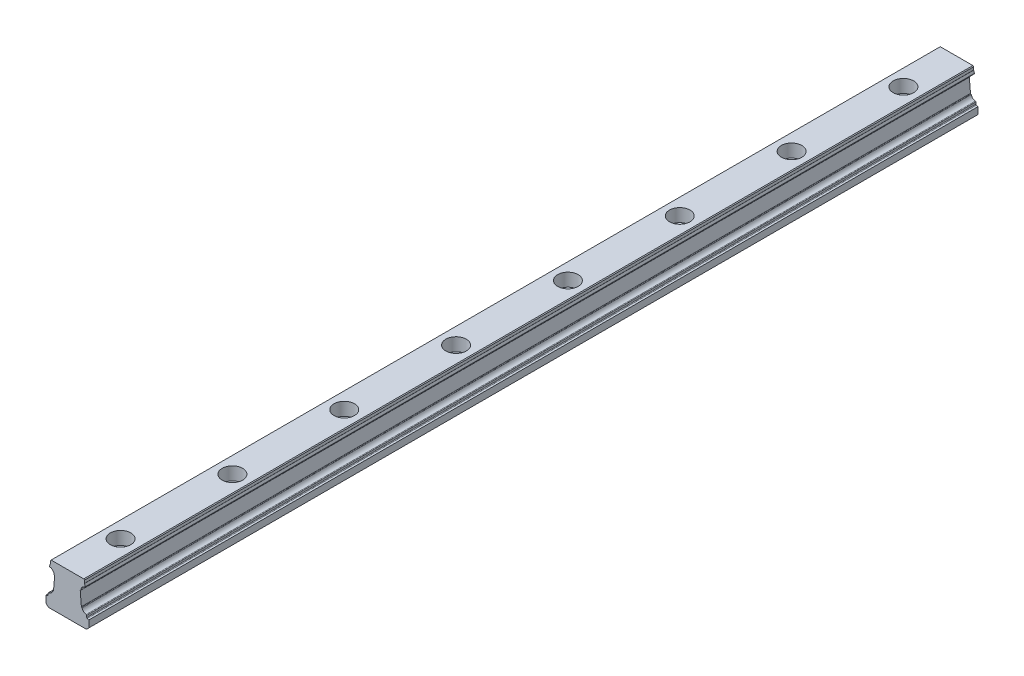
SolidWorks part; units mm, degrees
material "Alloy Steel"
ref_plane "Front Plane" through (0, 0, 0) normal (0, 0, 1) x (1, 0, 0)
ref_plane "Top Plane" through (0, 0, 0) normal (0, 1, 0) x (1, 0, 0)
ref_plane "Right Plane" through (0, 0, 0) normal (1, 0, 0) x (0, 0, -1)
sketch "Sketch1" plane through (0, 0, 0) normal (0, 0, 1) x (1, 0, 0)
  line L36 (7.4772, -2.1638) -> (6.8546, 4.9522)
  line L37 (9.5988, 8.2121) -> (9.1741, 9.3787)
  line L38 (9.15, 9.5155) -> (9.15, 10.95)
  line L39 (9.15, 10.95) -> (8.75, 11.35)
  line L40 (8.75, 11.35) -> (-8.75, 11.35)
  line L41 (-8.75, 11.35) -> (-9.15, 10.95)
  line L42 (-9.15, 10.95) -> (-9.15, 9.5155)
  line L43 (-9.1741, 9.3787) -> (-9.5988, 8.2121)
  line L44 (-6.8546, 4.9522) -> (-7.4772, -2.1638)
  line L45 (-10.3357, -4.8311) -> (-10.3357, -5.7311)
  line L46 (-10.6321, -6.1175) -> (-11.5, -6.35)
  line L47 (-11.5, -6.35) -> (-11.5, -10.05)
  line L48 (-11.5, -10.05) -> (-10.2, -11.35)
  line L49 (-10.2, -11.35) -> (10.2, -11.35)
  line L50 (10.2, -11.35) -> (11.5, -10.05)
  line L51 (11.5, -10.05) -> (11.5, -6.35)
  line L52 (11.5, -6.35) -> (10.6321, -6.1175)
  line L53 (10.3357, -5.7311) -> (10.3357, -4.8311)
  arc A40 (7.9064, -2.592) -> (7.6946, -2.3955) centre (7.656, -2.6495) ccw
  arc A41 (7.4772, -2.1638) -> (7.6946, -2.3955) centre (7.7332, -2.1414) ccw
  arc A42 (7.0239, 5.2165) -> (6.8546, 4.9522) centre (7.1107, 4.9746) ccw
  arc A43 (7.0239, 5.2165) -> (7.1938, 5.4446) centre (6.9372, 5.4585) ccw
  arc A44 (9.3228, 7.7549) -> (7.1938, 5.4446) centre (9.6562, 5.3115) ccw
  arc A45 (9.3228, 7.7549) -> (9.5988, 8.2121) centre (9.2764, 8.0947) ccw
  arc A46 (9.15, 9.5155) -> (9.1741, 9.3787) centre (9.55, 9.5155) ccw
  arc A47 (-9.1741, 9.3787) -> (-9.15, 9.5155) centre (-9.55, 9.5155) ccw
  arc A48 (-9.5988, 8.2121) -> (-9.3228, 7.7549) centre (-9.2764, 8.0947) ccw
  arc A49 (-7.1938, 5.4446) -> (-9.3228, 7.7549) centre (-9.6562, 5.3115) ccw
  arc A50 (-7.1938, 5.4446) -> (-7.0239, 5.2165) centre (-6.9372, 5.4585) ccw
  arc A51 (-6.8546, 4.9522) -> (-7.0239, 5.2165) centre (-7.1107, 4.9746) ccw
  arc A52 (-7.6946, -2.3955) -> (-7.4772, -2.1638) centre (-7.7332, -2.1414) ccw
  arc A53 (-7.6946, -2.3955) -> (-7.9064, -2.592) centre (-7.656, -2.6495) ccw
  arc A54 (-10.0314, -4.4903) -> (-7.9064, -2.592) centre (-10.3099, -2.0401) ccw
  arc A55 (-10.0314, -4.4903) -> (-10.3357, -4.8311) centre (-9.9927, -4.8311) ccw
  arc A56 (-10.6321, -6.1175) -> (-10.3357, -5.7311) centre (-10.7357, -5.7311) ccw
  arc A57 (10.3357, -5.7311) -> (10.6321, -6.1175) centre (10.7357, -5.7311) ccw
  arc A58 (10.3357, -4.8311) -> (10.0314, -4.4903) centre (9.9927, -4.8311) ccw
  arc A59 (7.9064, -2.592) -> (10.0314, -4.4903) centre (10.3099, -2.0401) ccw
extrude "Extrude1" add sketch "Sketch1" along normal mid plane 477
hole_wizard "CBORE for M6 Hex Socket Head Cap Screw1" positions "Sketch5" profile "Sketch4" counterbore size "M6" standard "Peddi DIN" end condition through all
sketch "Sketch5" plane through (0, 11.35, 0) normal (0, 1, 0) x (1, 0, 0)
  line L0 (0, 0) -> (0, -210) construction
  line L2 (8.75, -238.5) -> (-8.75, -238.5) construction
  point P0 (0, -210)
  dimension "D1" = 28.5
sketch "Sketch4" plane through (0, 11.35, 210) normal (1, 0, 0) x (0, 0, 1)
  line L0 (0, 0) -> (0, 22.7)
  line L1 (0, 22.7) -> (3.3, 22.7)
  line L3 (3.3, 22.7) -> (3.3, 7)
  line L4 (3.3, 7) -> (5.5, 7)
  line L5 (5.5, 7) -> (5.5, 0)
  line L7 (5.5, 0) -> (0, 0)
  line L11 (0, -6.35) -> (0, 107.95) construction
  dimension "Thru Hole Dia." = 6.6
  dimension "Thru Hole Depth" = 22.7
  dimension "C'Bore Dia." = 11
  dimension "C'Bore Depth" = 7
pattern_linear "LPattern2" count 8 spacing 60 along (0, 0, -1) of "CBORE for M6 Hex Socket Head Cap Screw1"
other "Freeze***"
